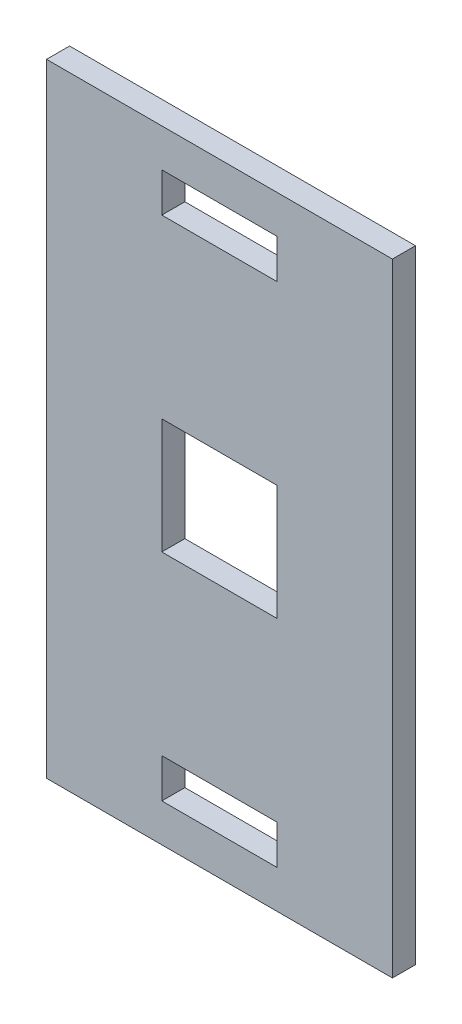
SolidWorks part; units mm, degrees
ref_plane "Front Plane" through (0, 0, 0) normal (0, 0, 1) x (1, 0, 0)
ref_plane "Top Plane" through (0, 0, 0) normal (0, 1, 0) x (1, 0, 0)
ref_plane "Right Plane" through (0, 0, 0) normal (1, 0, 0) x (0, 0, -1)
sketch "Sketch1" plane through (0, 0, 0) normal (0, 0, 1) x (1, 0, 0)
  line L1 (-15, -27) -> (15, -27)
  line L2 (-15, -27) -> (-15, 27)
  line L3 (-15, 27) -> (15, 27)
  line L4 (15, -27) -> (15, 27)
extrude "Plate_54x30" add sketch "Sketch1" along normal blind 2 from offset 0
sketch "Sketch2" plane through (0, 0, 0) normal (0, 0, 1) x (1, 0, 0)
  line L1 (-5, -5) -> (5, -5)
  line L2 (-5, -5) -> (-5, 5)
  line L3 (-5, 5) -> (5, 5)
  line L4 (5, -5) -> (5, 5)
extrude "Optical_Window_10x10" cut sketch "Sketch2" along normal blind 2.2 from offset 0.1
sketch "Sketch3" plane through (0, 0, 0) normal (0, 0, 1) x (1, 0, 0)
  line L1 (-5, -23.7) -> (5, -23.7)
  line L2 (-5, -23.7) -> (-5, -20.3)
  line L3 (-5, -20.3) -> (5, -20.3)
  line L4 (5, -23.7) -> (5, -20.3)
extrude "Vertical_M3_Adjustment_-1" cut sketch "Sketch3" along normal blind 2.2 from offset 0.1
sketch "Sketch4" plane through (0, 0, 0) normal (0, 0, 1) x (1, 0, 0)
  line L1 (-5, 20.3) -> (5, 20.3)
  line L2 (-5, 20.3) -> (-5, 23.7)
  line L3 (-5, 23.7) -> (5, 23.7)
  line L4 (5, 20.3) -> (5, 23.7)
extrude "Vertical_M3_Adjustment_1" cut sketch "Sketch4" along normal blind 2.2 from offset 0.1
